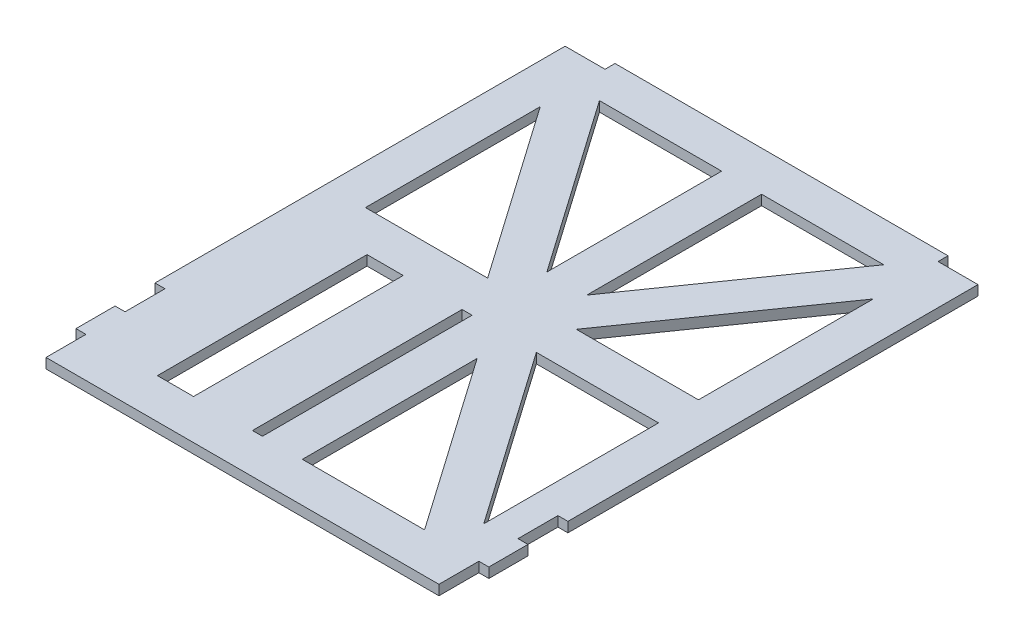
SolidWorks part; units mm, degrees
ref_plane "Front Plane" through (0, 0, 0) normal (0, 0, 1) x (1, 0, 0)
ref_plane "Top Plane" through (0, 0, 0) normal (0, 1, 0) x (1, 0, 0)
ref_plane "Right Plane" through (0, 0, 0) normal (1, 0, 0) x (0, 0, -1)
sketch "Sketch1" plane through (0, 0, 0) normal (0, 1, 0) x (1, 0, 0)
  line L0 (0, -85.5686) -> (0, 85.8814) construction
  line L1 (-52.96, 85.8814) -> (52.96, 85.8814)
  line L2 (-65.66, 82.7064) -> (-65.66, -47.7236)
  line L3 (-62.485, -85.5686) -> (62.485, -85.5686)
  line L4 (65.66, 82.7064) -> (65.66, -47.7236)
  line L5 (-65.66, 0.1564) -> (65.66, 0.1564) construction
  line L6 (-52.96, 6.5064) -> (-14.0978, 6.5064)
  line L7 (-45.2122, 73.1814) -> (-6.35, 73.1814)
  line L8 (-52.96, 62.0984) -> (-52.96, 6.5064)
  line L9 (-39.7545, -72.8686) -> (-28.2545, -72.8686)
  line L10 (52.96, 62.0984) -> (52.96, 6.5064)
  line L11 (-6.35, 73.1814) -> (-6.35, 17.5895)
  line L12 (6.35, 73.1814) -> (6.35, 17.5895)
  line L13 (14.0978, -6.1936) -> (52.96, -6.1936)
  line L14 (-52.96, 73.1814) -> (-6.35, 6.5064) construction
  line L15 (52.96, 73.1814) -> (6.35, 6.5064) construction
  line L16 (6.35, -6.1936) -> (52.96, -72.8686) construction
  line L17 (-52.96, 62.0984) -> (-14.0978, 6.5064)
  line L18 (-45.2122, 73.1814) -> (-6.35, 17.5895)
  line L19 (45.2122, 73.1814) -> (6.35, 17.5895)
  line L20 (52.96, 62.0984) -> (14.0978, 6.5064)
  line L21 (6.35, -17.2766) -> (45.2122, -72.8686)
  line L22 (14.0978, -6.1936) -> (52.96, -61.7855)
  line L23 (-34.0045, -6.1936) -> (-34.0045, -72.8686) construction
  line L24 (-39.7545, -6.1936) -> (-28.2545, -6.1936)
  line L25 (-39.7545, -6.1936) -> (-39.7545, -72.8686)
  line L27 (-28.2545, -6.1936) -> (-28.2545, -72.8686)
  line L28 (-65.66, 82.7064) -> (-52.96, 82.7064)
  line L29 (-52.96, 82.7064) -> (-52.96, 85.8814)
  line L30 (65.66, 82.7064) -> (52.96, 82.7064)
  line L31 (52.96, 82.7064) -> (52.96, 85.8814)
  line L32 (-65.66, -72.8686) -> (-62.485, -72.8686)
  line L33 (-62.485, -72.8686) -> (-62.485, -85.5686)
  line L34 (65.66, -72.8686) -> (62.485, -72.8686)
  line L35 (62.485, -72.8686) -> (62.485, -85.5686)
  line L36 (6.35, 73.1814) -> (45.2122, 73.1814)
  line L37 (-9.525, -6.1936) -> (-6.35, -6.1936)
  line L38 (-9.525, -6.1936) -> (-9.525, -72.8686)
  line L39 (-9.525, -72.8686) -> (-6.35, -72.8686)
  line L40 (-6.35, -6.1936) -> (-6.35, -72.8686)
  line L41 (14.0978, 6.5064) -> (52.96, 6.5064)
  line L42 (6.35, -17.2766) -> (6.35, -72.8686)
  line L43 (52.96, -6.1936) -> (52.96, -61.7855)
  line L45 (6.35, -72.8686) -> (45.2122, -72.8686)
  line L46 (-65.66, -47.7236) -> (-62.485, -47.7236)
  line L47 (-62.485, -47.7236) -> (-62.485, -60.4236)
  line L48 (-62.485, -60.4236) -> (-65.66, -60.4236)
  line L49 (65.66, -47.7236) -> (62.485, -47.7236)
  line L50 (62.485, -47.7236) -> (62.485, -60.4236)
  line L51 (62.485, -60.4236) -> (65.66, -60.4236)
  line L52 (-65.66, -60.4236) -> (-65.66, -72.8686)
  line L53 (65.66, -60.4236) -> (65.66, -72.8686)
  point P36 (-34.0045, -32.2513)
  dimension "D3" = 12.7
  dimension "D4" = 12.7
  dimension "D5" = 12.7
  dimension "D6" = 12.7
  dimension "D7" = 6.35
  dimension "D8" = 6.35
  dimension "D9" = 6.35
  dimension "D10" = 6.35
  dimension "D11" = 6.35
  dimension "D12" = 6.35
  dimension "D13" = 6.35
  dimension "D14" = 6.35
  dimension "D15" = 6.35
  dimension "D16" = 6.35
  dimension "D17" = 27.6545
  dimension "D18" = 11.5
  dimension "D19" = 12.7
  dimension "D20" = 12.7
  dimension "D21" = 3.175
  dimension "D22" = 12.7
  dimension "D23" = 12.7
  dimension "D24" = 12.7
  dimension "D25" = 3.175
  dimension "D26" = 3.175
  dimension "D27" = 3.175
  dimension "D28" = 12.7
  dimension "D29" = 6.35
  dimension "D30" = 130.43
  dimension "D31" = 12.7
  dimension "D32" = 12.7
  dimension "D33" = 130.43
extrude "Boss-Extrude1" add sketch "Sketch1" along normal blind 3.175
